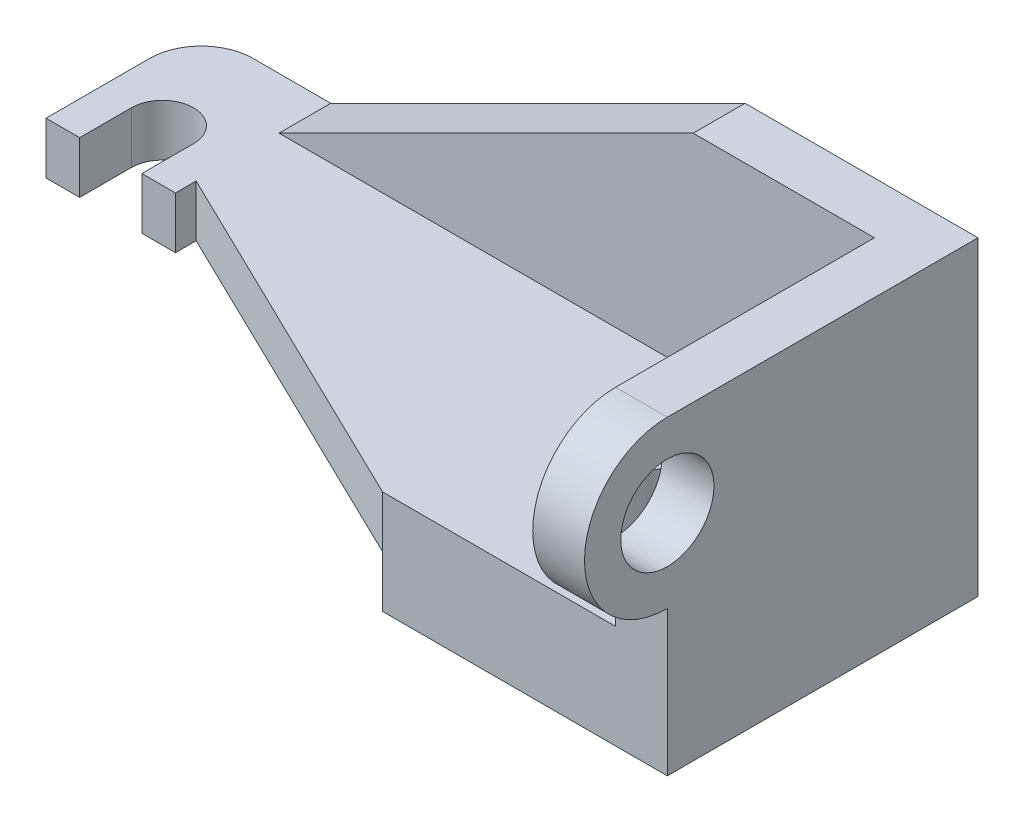
SolidWorks part; units mm, degrees
ref_plane "Front Plane" through (0, 0, 0) normal (0, 0, 1) x (1, 0, 0)
ref_plane "Top Plane" through (0, 0, 0) normal (0, 1, 0) x (1, 0, 0)
ref_plane "Right Plane" through (0, 0, 0) normal (1, 0, 0) x (0, 0, -1)
sketch "Sketch1" plane through (0, 0, 0) normal (0, 1, 0) x (1, 0, 0)
  line L0 (0, -36.7049) -> (55, -36.7049)
  line L1 (55, -36.7049) -> (55, 23.2951)
  line L2 (55, 23.2951) -> (-85, 23.2951)
  line L3 (-95, 13.2951) -> (-95, -6.7049)
  line L4 (-95, -6.7049) -> (-88.5, -6.7049)
  line L5 (-70, -6.7049) -> (-70, -2.7049)
  line L6 (-70, -2.7049) -> (0, -36.7049)
  line L7 (-76.5, -6.7049) -> (-70, -6.7049)
  line L8 (-76.5, -6.7049) -> (-76.5, 3.2951)
  line L10 (-88.5, 3.2951) -> (-88.5, -6.7049)
  arc A0 (-76.5, 3.2951) -> (-88.5, 3.2951) centre (-82.5, 3.2951) ccw
  arc A1 (-95, 13.2951) -> (-85, 23.2951) centre (-85, 13.2951) cw
  dimension "D1" = 10
extrude "Boss-Extrude1" add sketch "Sketch1" along normal blind 10
ref_plane "Plane1" through (55, 0, 0) normal (-1, 0, 0) x (0, 0, 1)
sketch "Sketch2" plane through (55, 0, 0) normal (-1, 0, 0) x (0, 0, 1)
  line L0 (-23.2951, 10) -> (36.7049, 10)
  line L1 (36.7049, 10) -> (36.7049, 18)
  line L2 (36.7049, 50) -> (-23.2951, 50)
  line L3 (-23.2951, 50) -> (-23.2951, 10)
  arc A0 (36.7049, 18) -> (36.7049, 50) centre (36.7049, 34) ccw
  circle A1 centre (36.7049, 34) radius 9
extrude "Boss-Extrude2" add sketch "Sketch2" along normal blind 10
ref_plane "Plane2" through (0, 0, -23.2951) normal (0, 0, 1) x (1, 0, 0)
sketch "Sketch3" plane through (0, 0, -23.2951) normal (0, 0, 1) x (1, 0, 0)
  line L0 (45, 10) -> (-70, 10)
  line L1 (45, 10) -> (-85, 10) construction
  line L2 (45, 11.1654) -> (45, 50)
  line L3 (45, 50) -> (45, 10) construction
  line L4 (45, 50) -> (10, 50)
  line L5 (10, 50) -> (-70, 10)
  line L12 (-85, 0) -> (55, 0)
  line L13 (-85, 10) -> (-85, 0)
  line L14 (45, 10) -> (-85, 10)
  line L15 (45, 50) -> (45, 10)
  line L16 (55, 50) -> (45, 50)
  line L17 (55, 0) -> (55, 50)
  line L21 (45, 11.1654) -> (45, 10)
  dimension "D1" = 0
extrude "Boss-Extrude3" add sketch "Sketch3" along normal blind 10
sketch "Sketch4" plane through (0, 0, 0) normal (0, -1, 0) x (-1, 0, 0)
  line L0 (0, -36.7049) -> (0, 23.2951)
  line L1 (-55, 23.2951) -> (85, 23.2951) construction
  line L2 (0, 23.2951) -> (-55, 23.2951)
  line L3 (-55, 23.2951) -> (-55, -36.7049)
  line L4 (-55, -36.7049) -> (0, -36.7049)
extrude "Boss-Extrude4" add sketch "Sketch4" along normal blind 10
sketch "Sketch5" plane through (0, 10, 0) normal (0, 1, 0) x (1, 0, 0)
  line L0 (0, -36.7049) -> (45, -36.7049) construction
  line L1 (45, 13.2951) -> (45, -36.7049) construction
  circle A0 centre (30, -11.7049) radius 9
  dimension "D1" = 18
  dimension "D2" = 25
  dimension "D3" = 15
extrude "Cut-Extrude1" cut sketch "Sketch5" against normal blind 38
